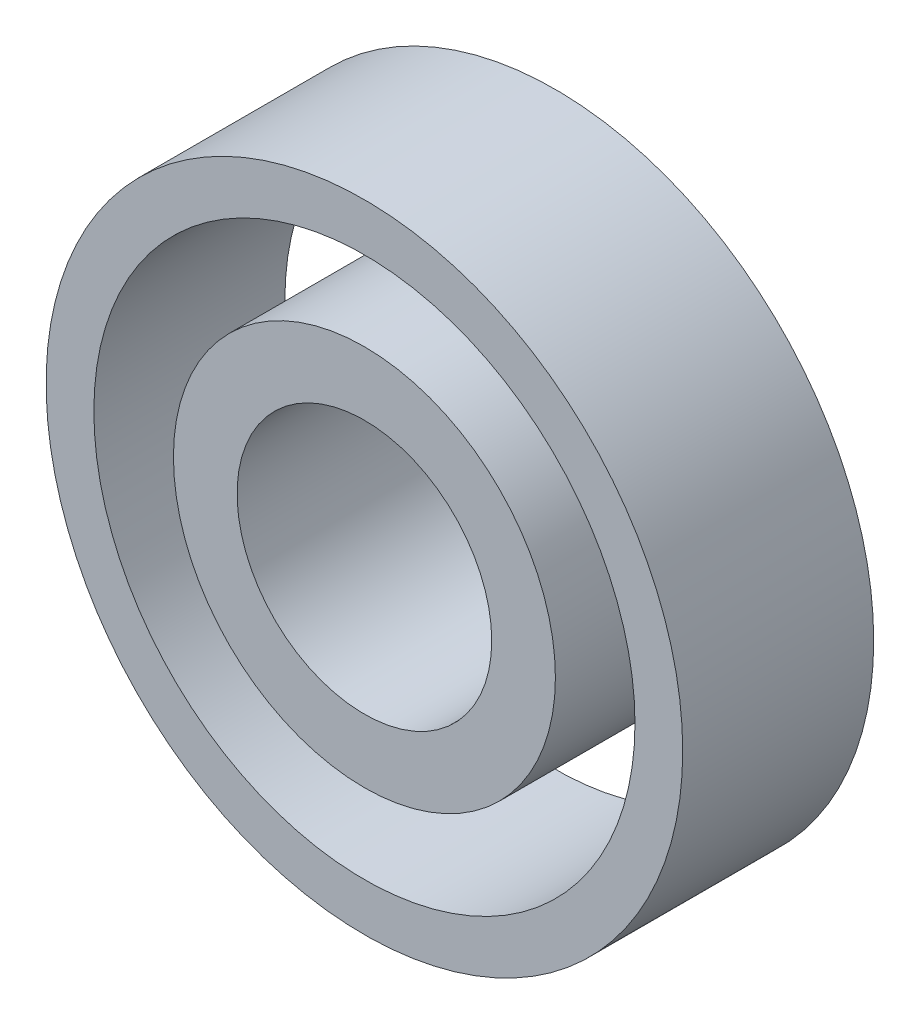
SolidWorks part; units mm, degrees
ref_plane "Front Plane" through (0, 0, 0) normal (0, 0, 1) x (1, 0, 0)
ref_plane "Top Plane" through (0, 0, 0) normal (0, 1, 0) x (1, 0, 0)
ref_plane "Right Plane" through (0, 0, 0) normal (1, 0, 0) x (0, 0, -1)
sketch "Sketch1" plane through (0, 0, 0) normal (0, 0, 1) x (1, 0, 0)
  circle A0 centre (0, 0) radius 20
  circle A1 centre (0, 0) radius 17
  dimension "D1" = 40
  dimension "D2" = 34
extrude "Boss-Extrude1" add sketch "Sketch1" against normal blind 12
sketch "Sketch2" plane through (0, 0, 0) normal (0, 0, 1) x (1, 0, 0)
  circle A0 centre (0, 0) radius 12
  circle A1 centre (0, 0) radius 8
  dimension "D1" = 24
  dimension "D2" = 16
extrude "Boss-Extrude2" add sketch "Sketch2" against normal blind 12 separate body
